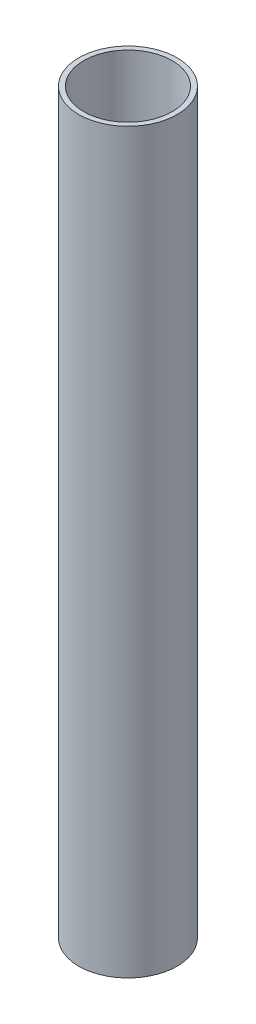
SolidWorks part; units mm, degrees
material "AISI 316 Stainless Steel Sheet (SS)"
ref_plane "Front Plane" through (0, 0, 0) normal (0, 0, 1) x (1, 0, 0)
ref_plane "Top Plane" through (0, 0, 0) normal (0, 1, 0) x (1, 0, 0)
ref_plane "Right Plane" through (0, 0, 0) normal (1, 0, 0) x (0, 0, -1)
sketch "Sketch2" plane through (0, 0, 0) normal (0, 1, 0) x (1, 0, 0)
  circle A0 centre (0, 0) radius 10
  circle A1 centre (0, 0) radius 9
  dimension "D1" = 20
  dimension "D2" = 1
extrude "Boss-Extrude1" add sketch "Sketch2" along normal mid plane 150
